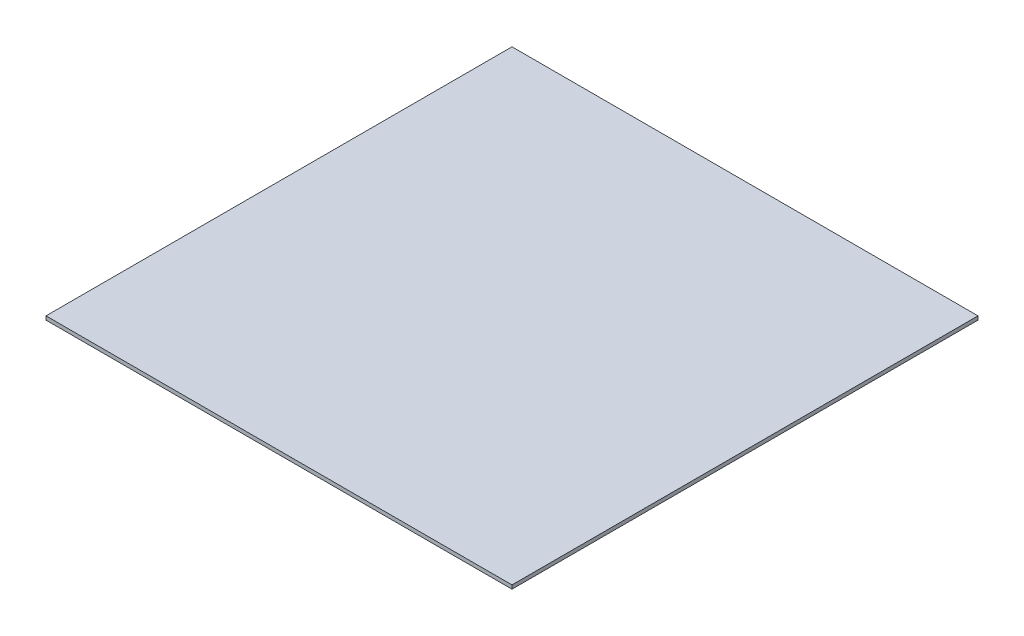
SolidWorks part; units mm, degrees
material "Perspex (TM) GS Acrylic Cast Sheet"
ref_plane "Front Plane" through (0, 0, 0) normal (0, 0, 1) x (1, 0, 0)
ref_plane "Top Plane" through (0, 0, 0) normal (0, 1, 0) x (1, 0, 0)
ref_plane "Right Plane" through (0, 0, 0) normal (1, 0, 0) x (0, 0, -1)
sketch "Sketch1" plane through (0, 0, 0) normal (0, 1, 0) x (1, 0, 0)
  line L1 (-250, -250) -> (250, -250)
  line L2 (-250, -250) -> (-250, 250)
  line L3 (-250, 250) -> (250, 250)
  line L4 (250, -250) -> (250, 250)
  line L5 (-250, -250) -> (250, 250) construction
  line L6 (-250, 250) -> (250, -250) construction
  point P0 (0, 0)
  dimension "D1" = 500
  dimension "D2" = 500
extrude "Boss-Extrude1" add sketch "Sketch1" along normal blind 4
sketch "Sketch2" plane through (0, 0, 0) normal (0, -1, 0) x (-1, 0, 0)
  line L1 (246, 246) -> (-246, 246)
  line L2 (246, 246) -> (246, -246)
  line L3 (246, -246) -> (-246, -246)
  line L4 (-246, 246) -> (-246, -246)
  line L5 (246, 246) -> (-246, -246) construction
  line L6 (246, -246) -> (-246, 246) construction
  line L7 (-250, -250) -> (-250, 250) construction
  line L8 (-250, 250) -> (250, 250) construction
  point P0 (0, 0)
  dimension "D1" = 4
  dimension "D2" = 4
extrude "Boss-Extrude2" add sketch "Sketch2" along normal blind 4
